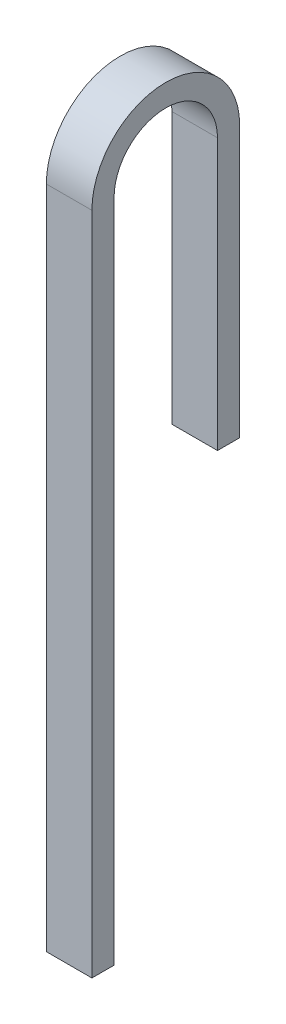
SolidWorks part; units mm, degrees
material "ABS"
ref_plane "Płaszczyzna przednia" through (0, 0, 0) normal (0, 0, 1) x (1, 0, 0)
ref_plane "Płaszczyzna górna" through (0, 0, 0) normal (0, 1, 0) x (1, 0, 0)
ref_plane "Płaszczyzna prawa" through (0, 0, 0) normal (1, 0, 0) x (0, 0, -1)
sketch "Szkic1" plane through (0, 0, 0) normal (1, 0, 0) x (0, 0, -1)
  line L0 (0, 0) -> (0, 220)
  line L1 (-120, 220) -> (-120, -320)
  arc A0 (0, 220) -> (-120, 220) centre (-60, 220) ccw
  dimension "D1" = 120
  dimension "D2" = 220
  dimension "D3" = 540
extrude "Wyciągnięcie-cienka ścianka1" add sketch "Szkic1" along normal mid plane 37 thin thin type one direction reverse wall 18
